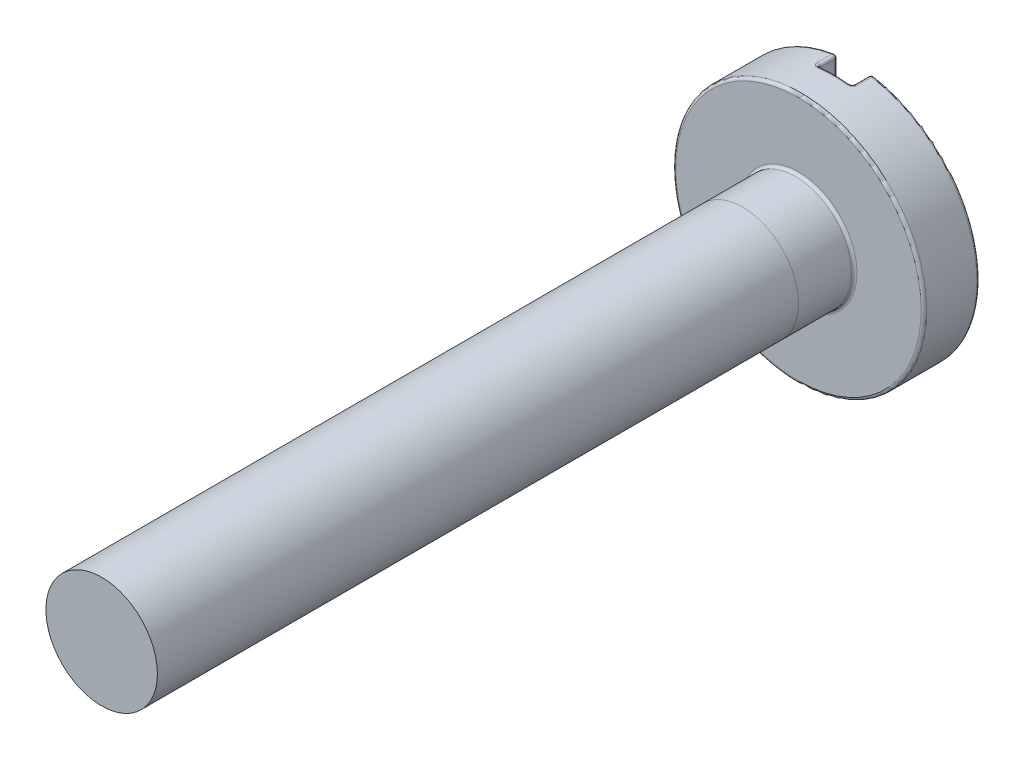
SolidWorks part; units mm, degrees
ref_plane "Front Plane" through (0, 0, 0) normal (0, 0, 1) x (1, 0, 0)
ref_plane "Top Plane" through (0, 0, 0) normal (0, 1, 0) x (1, 0, 0)
ref_plane "Right Plane" through (0, 0, 0) normal (1, 0, 0) x (0, 0, -1)
sketch "Sketch1" plane through (0, 0, 0) normal (0, 0, 1) x (1, 0, 0)
  circle A0 centre (0, 0) radius 1
  dimension "D1" = 2
extrude "Boss-Extrude1" add sketch "Sketch1" along normal blind 12.5
sketch "Sketch2" plane through (0, 0, 0) normal (0, 0, 1) x (1, 0, 0)
  circle A2 centre (0, 0) radius 2.25
  circle A3 centre (0, 0) radius 2.25
  dimension "D1" = 1.25
extrude "Boss-Extrude2" add sketch "Sketch2" against normal blind 1
sketch "Sketch3" plane through (0, 0, -1) normal (0, 0, -1) x (-1, 0, 0)
  line L1 (0.3, -6.7813) -> (-0.3, -6.7813)
  line L2 (0.3, -6.7813) -> (0.3, 6.7813)
  line L3 (0.3, 6.7813) -> (-0.3, 6.7813)
  line L4 (-0.3, -6.7813) -> (-0.3, 6.7813)
  line L5 (0.3, -6.7813) -> (-0.3, 6.7813) construction
  line L6 (0.3, 6.7813) -> (-0.3, -6.7813) construction
  point P0 (0, 0)
  dimension "D1" = 0.6
extrude "Cut-Extrude1" cut sketch "Sketch3" against normal blind 0.35
fillet "Fillet1" radius 0.05 12 edges at (-0.3, -2.2299, -0.825) (-0.3, 2.2299, -0.825) (0.3, 2.2299, -0.825) (0.3, -2.2299, -0.825) (0, 2.25, -0.65) (0, -2.25, -0.65) (0.3, 0, -0.65) (-0.3, 0, -0.65) (-0.3, 0, -1) (-2.25, 0, -1) (0.3, 0, -1) (2.25, 0, -1)
fillet "Fillet2" radius 0.05 2 edges at (2.25, 0, 0) (1, 0, 0)
sketch "Sketch4" plane through (0, 0, 0) normal (1, 0, 0) x (0, 0, -1)
  line L0 (-1, -3.6683) -> (-1, 4.4314)
  line L1 (-12.5, 1) -> (-12.5, -1) construction
  dimension "D1" = 11.5
split line "Split Line1"
